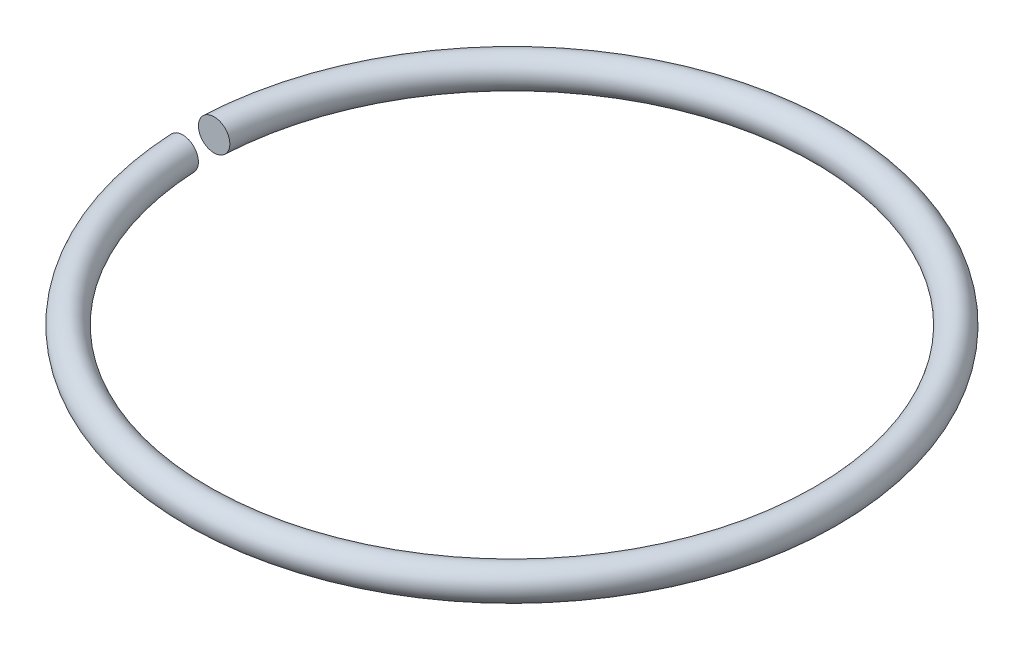
SolidWorks part; units mm, degrees
material "1.5805 (10NiCr5-4)"
ref_plane "Спереди" through (0, 0, 0) normal (0, 0, 1) x (1, 0, 0)
ref_plane "Сверху" through (0, 0, 0) normal (0, 1, 0) x (1, 0, 0)
ref_plane "Справа" through (0, 0, 0) normal (1, 0, 0) x (0, 0, -1)
sketch "Эскиз1" plane through (0, 0, 0) normal (0, 0, 1) x (1, 0, 0)
  line L0 (0, 0) -> (0, 5.376) construction
  circle A0 centre (-20, 1) radius 1
  dimension "D1" = 2
  dimension "D3" = 1
  dimension "D2" = 20
revolve "Повернуть1" add sketch "Эскиз1" angle 360 about L0
sketch "Эскиз2" plane through (0, 0, 0) normal (0, 1, 0) x (1, 0, 0)
  line L0 (0, 0) -> (-16.7656, 0) construction
  line L1 (-23.1189, 1) -> (-7.1672, 1)
  line L2 (-23.1189, 1) -> (-23.1189, -1)
  line L3 (-23.1189, -1) -> (-7.1672, -1)
  line L4 (-7.1672, 1) -> (-7.1672, -1)
  dimension "D1" = 1
  dimension "D2" = 1
extrude "Вырез-Вытянуть1" cut sketch "Эскиз2" against normal through all and the other way through all
